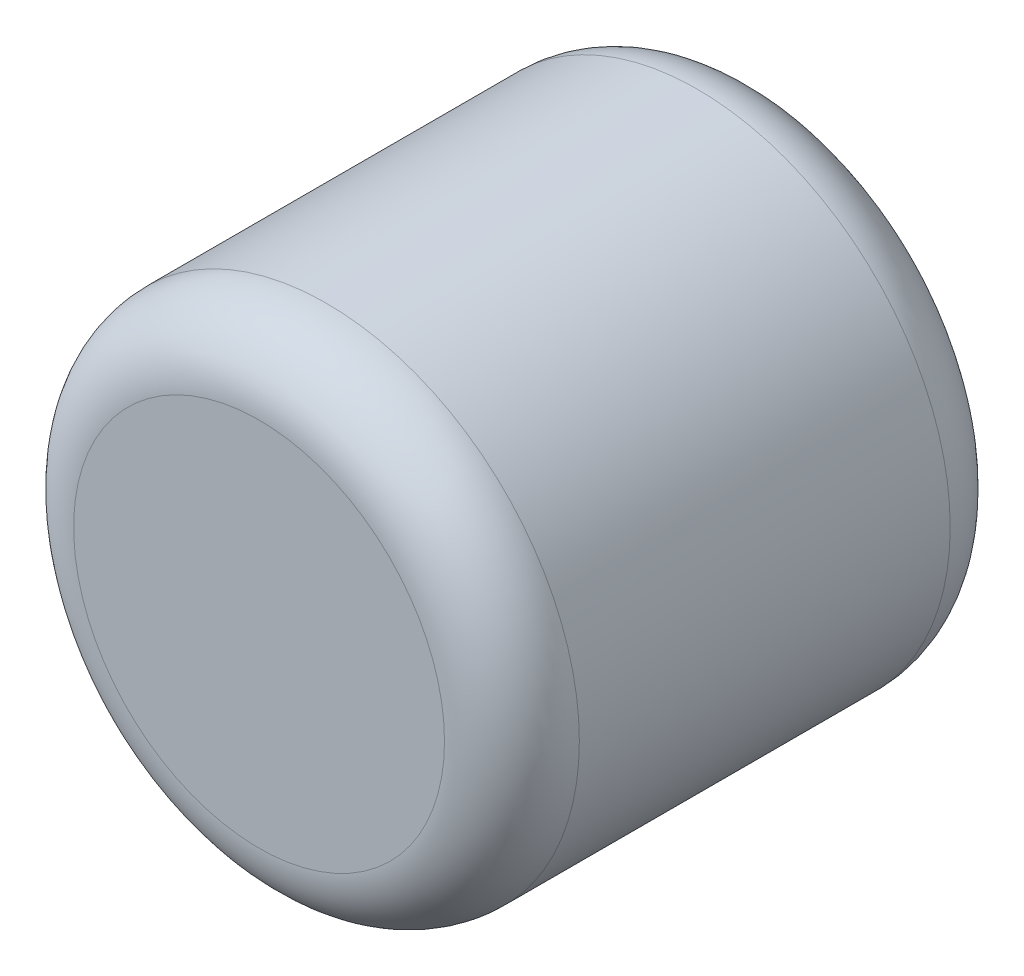
SolidWorks part; units mm, degrees
material "NEOPRENE"
ref_plane "Front Plane" through (0, 0, 0) normal (0, 0, 1) x (1, 0, 0)
ref_plane "Top Plane" through (0, 0, 0) normal (0, 1, 0) x (1, 0, 0)
ref_plane "Right Plane" through (0, 0, 0) normal (1, 0, 0) x (0, 0, -1)
sketch "Sketch1" plane through (0, 0, 0) normal (0, 0, 1) x (1, 0, 0)
  circle A0 centre (0, 0) radius 15
extrude "Boss-Extrude1" add sketch "Sketch1" along normal blind 30 contours A0
fillet "Fillet1" radius 4 1 edges at (15, 0, 30)
fillet "Fillet2" radius 4 1 edges at (15, 0, 0)
